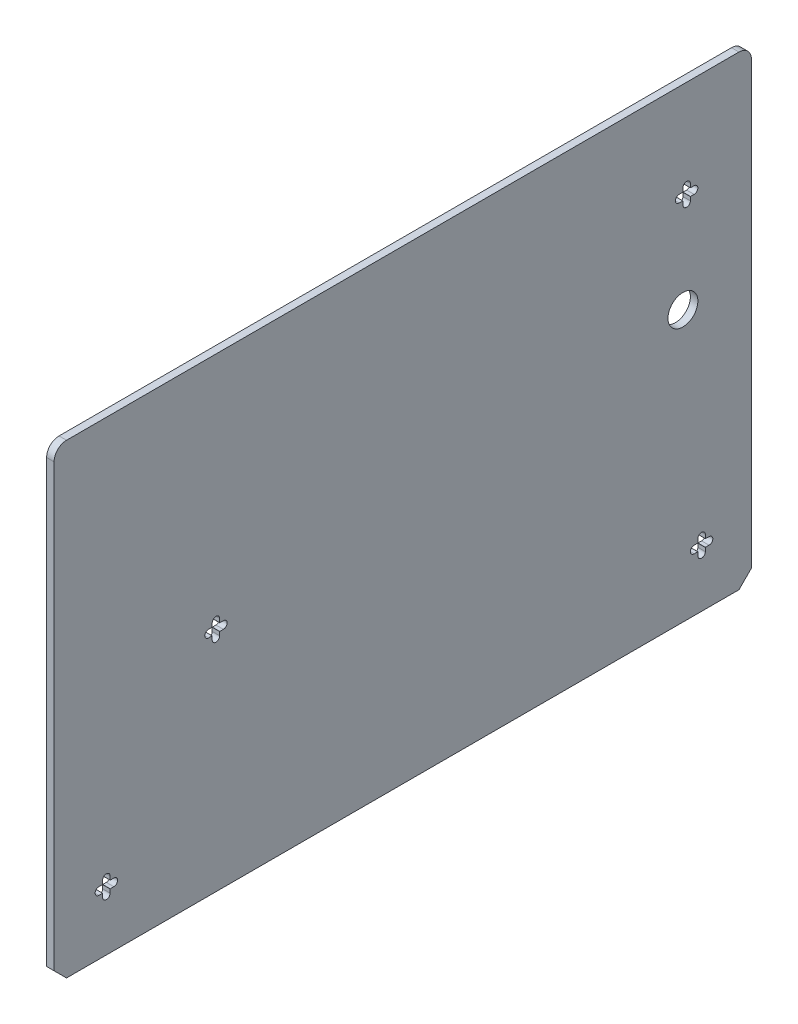
SolidWorks part; units mm, degrees
ref_plane "Front Plane" through (0, 0, 0) normal (0, 0, 1) x (1, 0, 0)
ref_plane "Top Plane" through (0, 0, 0) normal (0, 1, 0) x (1, 0, 0)
ref_plane "Right Plane" through (0, 0, 0) normal (1, 0, 0) x (0, 0, -1)
sketch "Sketch1" plane through (0, 0, 0) normal (1, 0, 0) x (0, -1, 0)
  line L0 (-52.95, 115.5) -> (-51.5, 115.5)
  line L1 (-52.95, 112.5) -> (-51.5, 112.5)
  line L2 (-56, 117) -> (-56, 115.55)
  line L3 (-56, 111) -> (-56, 112.45)
  line L4 (-53, 115.55) -> (-53, 117)
  line L5 (-57.5, 115.5) -> (-56.05, 115.5)
  line L6 (-57.5, 112.5) -> (-56.05, 112.5)
  line L7 (-53, 111) -> (-53, 112.45)
  line L42 (-93.5, 135) -> (-93.5, -135)
  line L43 (88.5, 140) -> (-88.5, 140)
  line L44 (93.5, 135) -> (88.5, 140)
  line L45 (93.5, -135) -> (93.5, 135)
  line L46 (93.5, -135) -> (88.5, -140)
  line L115 (67.5, 121.5) -> (68.95, 121.5)
  line L116 (69, 123) -> (69, 121.55)
  line L117 (67.5, 118.5) -> (68.95, 118.5)
  line L118 (69, 117) -> (69, 118.45)
  line L119 (72, 117) -> (72, 118.45)
  line L120 (72.05, 118.5) -> (73.5, 118.5)
  line L121 (72.05, 121.5) -> (73.5, 121.5)
  line L122 (72, 121.55) -> (72, 123)
  line L155 (-88.5, -140) -> (88.5, -140)
  line L156 (3.75, -72) -> (3.75, -73.45)
  line L157 (5.25, -73.5) -> (3.8, -73.5)
  line L158 (0.75, -72) -> (0.75, -73.45)
  line L159 (-0.75, -73.5) -> (0.7, -73.5)
  line L160 (-0.75, -76.5) -> (0.7, -76.5)
  line L161 (0.75, -76.55) -> (0.75, -78)
  line L162 (3.75, -76.55) -> (3.75, -78)
  line L163 (3.8, -76.5) -> (5.25, -76.5)
  line L164 (71.25, -116) -> (71.25, -117.45)
  line L165 (72.75, -117.5) -> (71.3, -117.5)
  line L166 (68.25, -116) -> (68.25, -117.45)
  line L167 (66.75, -117.5) -> (68.2, -117.5)
  line L168 (66.75, -120.5) -> (68.2, -120.5)
  line L169 (68.25, -120.55) -> (68.25, -122)
  line L170 (71.25, -120.55) -> (71.25, -122)
  line L171 (71.3, -120.5) -> (72.75, -120.5)
  line L193 (0, -140) -> (0, 140) construction
  line L194 (-93.5, 0) -> (93.5, 0) construction
  arc A0 (-51.5, 112.5) -> (-51.5, 115.5) centre (-51.5, 114) ccw
  arc A1 (-52.95, 112.5) -> (-53, 112.45) centre (-52.95, 112.45) ccw
  arc A2 (-53, 115.55) -> (-52.95, 115.5) centre (-52.95, 115.55) ccw
  arc A3 (-56, 111) -> (-53, 111) centre (-54.5, 111) ccw
  arc A4 (-56.05, 115.5) -> (-56, 115.55) centre (-56.05, 115.55) ccw
  arc A5 (-53, 117) -> (-56, 117) centre (-54.5, 117) ccw
  arc A6 (-57.5, 115.5) -> (-57.5, 112.5) centre (-57.5, 114) ccw
  arc A7 (-56, 112.45) -> (-56.05, 112.5) centre (-56.05, 112.45) ccw
  circle A8 centre (-15.138, 112.5) radius 6
  arc A43 (-93.5, -135) -> (-88.5, -140) centre (-88.5, -135) ccw
  arc A44 (-88.5, 140) -> (-93.5, 135) centre (-88.5, 135) ccw
  arc A110 (67.5, 121.5) -> (67.5, 118.5) centre (67.5, 120) ccw
  arc A111 (73.5, 118.5) -> (73.5, 121.5) centre (73.5, 120) ccw
  arc A112 (69, 117) -> (72, 117) centre (70.5, 117) ccw
  arc A113 (72, 123) -> (69, 123) centre (70.5, 123) ccw
  arc A114 (68.95, 121.5) -> (69, 121.55) centre (68.95, 121.55) ccw
  arc A115 (69, 118.45) -> (68.95, 118.5) centre (68.95, 118.45) ccw
  arc A116 (72.05, 118.5) -> (72, 118.45) centre (72.05, 118.45) ccw
  arc A117 (72, 121.55) -> (72.05, 121.5) centre (72.05, 121.55) ccw
  arc A150 (3.75, -72) -> (0.75, -72) centre (2.25, -72) ccw
  arc A151 (0.75, -78) -> (3.75, -78) centre (2.25, -78) ccw
  arc A152 (-0.75, -73.5) -> (-0.75, -76.5) centre (-0.75, -75) ccw
  arc A153 (5.25, -76.5) -> (5.25, -73.5) centre (5.25, -75) ccw
  arc A154 (3.75, -73.45) -> (3.8, -73.5) centre (3.8, -73.45) ccw
  arc A155 (0.7, -73.5) -> (0.75, -73.45) centre (0.7, -73.45) ccw
  arc A156 (0.75, -76.55) -> (0.7, -76.5) centre (0.7, -76.55) ccw
  arc A157 (3.8, -76.5) -> (3.75, -76.55) centre (3.8, -76.55) ccw
  arc A158 (71.25, -116) -> (68.25, -116) centre (69.75, -116) ccw
  arc A159 (66.75, -117.5) -> (66.75, -120.5) centre (66.75, -119) ccw
  arc A160 (72.75, -120.5) -> (72.75, -117.5) centre (72.75, -119) ccw
  arc A161 (71.25, -117.45) -> (71.3, -117.5) centre (71.3, -117.45) ccw
  arc A162 (68.2, -117.5) -> (68.25, -117.45) centre (68.2, -117.45) ccw
  arc A163 (68.25, -120.55) -> (68.2, -120.5) centre (68.2, -120.55) ccw
  arc A164 (71.3, -120.5) -> (71.25, -120.55) centre (71.3, -120.55) ccw
  arc A165 (68.25, -122) -> (71.25, -122) centre (69.75, -122) ccw
  dimension "D1" = 12
extrude "Boss-Extrude1" add sketch "Sketch1" along normal blind 3
